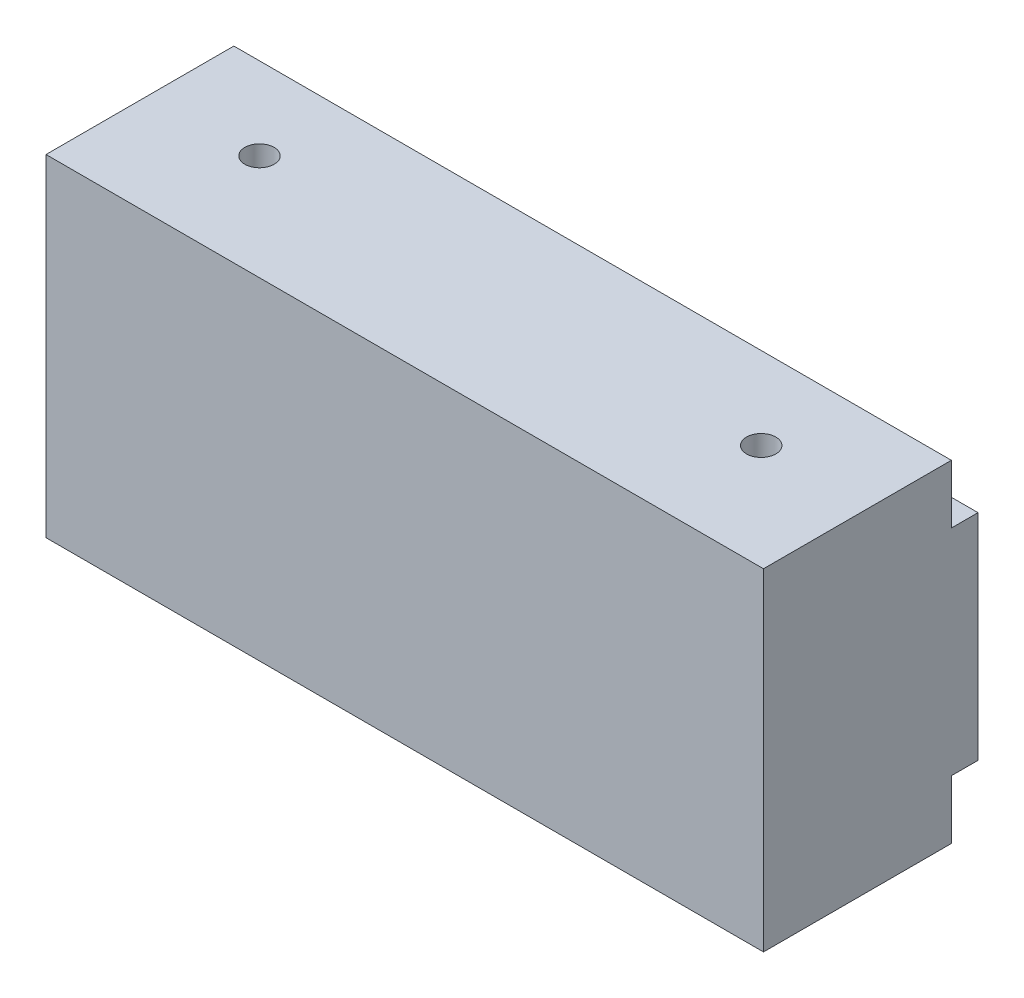
SolidWorks part; units mm, degrees
material "Subpack"
ref_plane "X-Y Datum" through (0, 0, 0) normal (0, 0, 1) x (1, 0, 0)
ref_plane "X-Z Datum" through (0, 0, 0) normal (0, 1, 0) x (1, 0, 0)
ref_plane "Y-Z Datum" through (0, 0, 0) normal (1, 0, 0) x (0, 0, -1)
sketch "Sketch1" plane through (0, 0, 0) normal (0, 1, 0) x (1, 0, 0)
  line L1 (0, 0) -> (310.6395, 0)
  line L2 (0, 0) -> (0, 92.8692)
  line L3 (0, 92.8692) -> (310.6395, 92.8692)
  line L4 (310.6395, 0) -> (310.6395, 92.8692)
  dimension "D1" = 92.8692
  dimension "D2" = 310.6395
extrude "Boss-Extrude1" add sketch "Sketch1" along normal blind 143.6878
sketch "Sketch2" plane through (0, 143.6878, 0) normal (0, 1, 0) x (1, 0, 0)
  line L0 (0, 45.72) -> (0, 0) construction
  line L1 (0, 92.8692) -> (0, 0) construction
  line L2 (0, 45.72) -> (46.7106, 45.72) construction
  line L3 (155.3197, 92.8692) -> (155.3197, -12.4635) construction
  line L4 (310.6395, 92.8692) -> (0, 92.8692) construction
  circle A0 centre (46.7106, 45.72) radius 6.35
  circle A1 centre (263.9289, 45.72) radius 6.35
  dimension "D1" = 45.72
extrude "Cut-Extrude1" cut sketch "Sketch2" against normal through all
sketch "Sketch3" plane through (0, 143.6878, 0) normal (0, 1, 0) x (1, 0, 0)
  line L0 (46.7106, 45.72) -> (46.7106, 92.8692) construction
  line L1 (310.6395, 92.8692) -> (0, 92.8692) construction
  line L2 (46.7106, 45.72) -> (46.7106, 0) construction
  line L3 (0, 0) -> (310.6395, 0) construction
  line L9 (0, 46.4346) -> (347.5244, 46.4346) construction
  line L10 (0, 92.8692) -> (0, 0) construction
  line L11 (0, 81.3384) -> (310.8274, 81.3384)
  line L12 (310.8274, 94.0384) -> (310.8274, 81.3384)
  line L13 (0, 94.0384) -> (310.8274, 94.0384)
  line L14 (0, 94.0384) -> (0, 81.3384)
extrude "Cut-Extrude2" cut sketch "Sketch3" against normal blind 25.4
ref_plane "Plane1" through (0, 71.8439, 0) normal (0, 1, 0) x (1, 0, 0)
mirror "Mirror1" about plane through (0, 71.8439, 0) normal (0, 1, 0) of "Cut-Extrude2"
ref_plane "Plane2" through (0, 0, -46.4346) normal (0, 0, 1) x (1, 0, 0)
